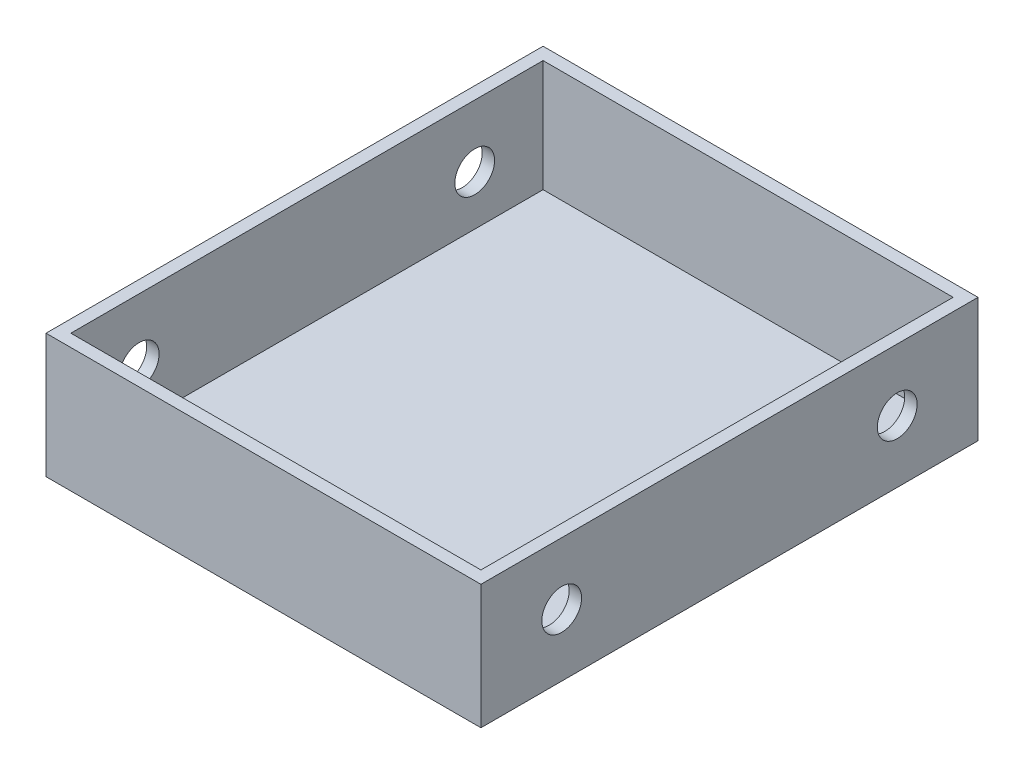
SolidWorks part; units mm, degrees
ref_plane "前视基准面" through (0, 0, 0) normal (0, 0, 1) x (1, 0, 0)
ref_plane "上视基准面" through (0, 0, 0) normal (0, 1, 0) x (1, 0, 0)
ref_plane "右视基准面" through (0, 0, 0) normal (1, 0, 0) x (0, 0, -1)
sketch "草图1" plane through (0, 0, 0) normal (0, 1, 0) x (1, 0, 0)
  line L1 (0, 0) -> (35, 0)
  line L2 (0, 0) -> (0, 40)
  line L3 (0, 40) -> (35, 40)
  line L4 (35, 0) -> (35, 40)
  dimension "D1" = 35
  dimension "D2" = 40
extrude "凸台-拉伸1" add sketch "草图1" along normal blind 10
shell "抽壳1" thickness 1
sketch "草图2" plane through (0, 0, 0) normal (-1, 0, 0) x (0, 0, 1)
  line L0 (-40, 5) -> (0, 5) construction
  line L1 (-40, 10) -> (-40, 0) construction
  line L2 (0, 10) -> (0, 0) construction
  line L3 (-20, 10) -> (-20, 0) construction
  line L4 (-40, 10) -> (0, 10) construction
  line L5 (-40, 0) -> (0, 0) construction
  circle A1 centre (-33.5, 5) radius 1.6
  circle A2 centre (-6.5, 5) radius 1.6
  dimension "D1" = 3.2
  dimension "D2" = 27
extrude "切除-拉伸1" cut sketch "草图2" against normal through all
